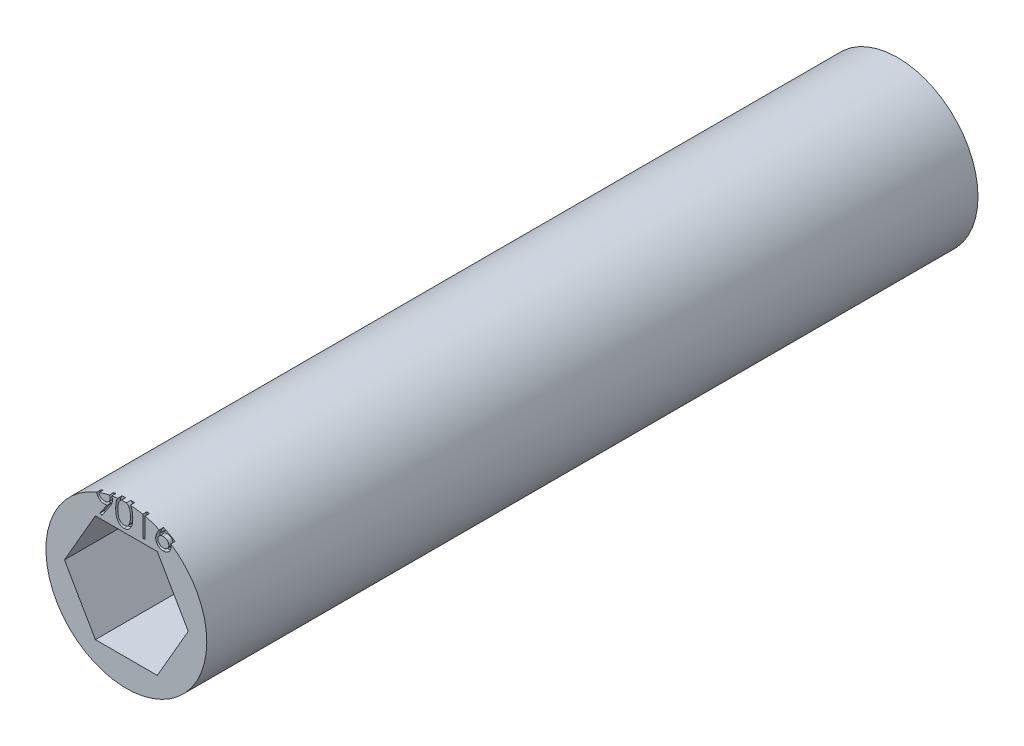
SolidWorks part; units mm, degrees
material "ABS"
ref_plane "Front Plane" through (0, 0, 0) normal (0, 0, 1) x (1, 0, 0)
ref_plane "Top Plane" through (0, 0, 0) normal (0, 1, 0) x (1, 0, 0)
ref_plane "Right Plane" through (0, 0, 0) normal (1, 0, 0) x (0, 0, -1)
sketch "Sketch1" plane through (0, 0, 0) normal (0, 0, 1) x (1, 0, 0)
  line L1 (-2.9329, -5.08) -> (2.9329, -5.08)
  line L2 (2.9329, -5.08) -> (5.8659, 0)
  line L3 (5.8659, 0) -> (2.9329, 5.08)
  line L4 (2.9329, 5.08) -> (-2.9329, 5.08)
  line L5 (-2.9329, 5.08) -> (-5.8659, 0)
  line L6 (-5.8659, 0) -> (-2.9329, -5.08)
  circle A0 centre (0, 0) radius 5.08 construction
  circle A1 centre (0, 0) radius 7.62
  dimension "D1" = 10.16
  dimension "D2" = 15.24
extrude "Boss-Extrude1" add sketch "Sketch1" along normal blind 73.0758 contours A1 L6 L5 L4 L3 L2 L1
sketch "Sketch3" plane through (0, 0, 73.0758) normal (0, 0, 1) x (1, 0, 0)
  line L0 (-2.9329, 5.4769) -> (2.9329, 5.4769) construction
  line L1 (2.9329, 5.08) -> (-2.9329, 5.08) construction
  text T0 "9016\r\n" font "Century Gothic" height 2.3813
  dimension "D1" = 0.3969
extrude "Cut-Extrude1" cut sketch "Sketch3" against normal blind 0.4
